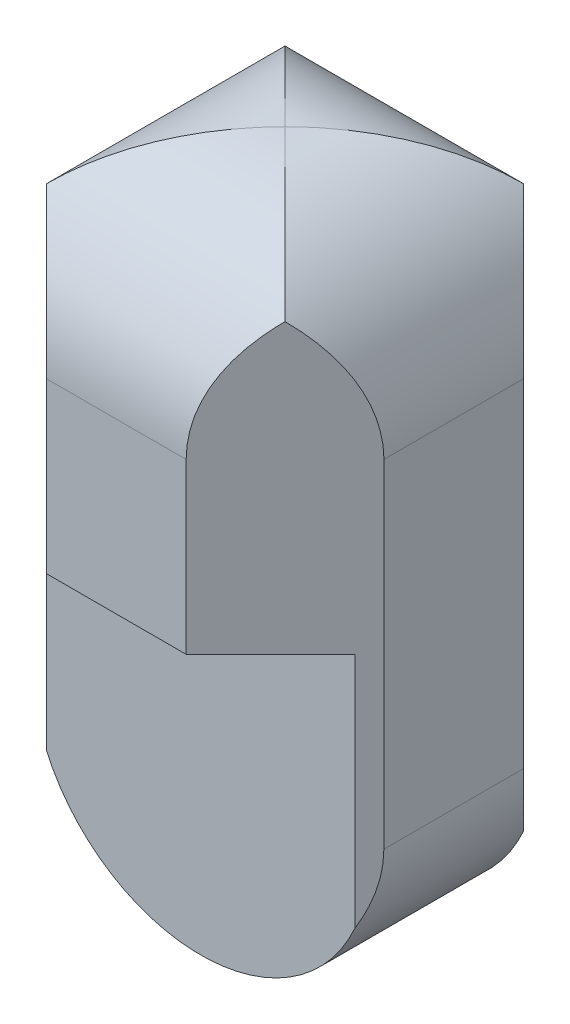
SolidWorks part; units mm, degrees
ref_plane "Front" through (0, 0, 0) normal (0, 0, 1) x (1, 0, 0)
ref_plane "Top" through (0, 0, 0) normal (0, 1, 0) x (1, 0, 0)
ref_plane "Right" through (0, 0, 0) normal (1, 0, 0) x (0, 0, -1)
sketch "草图1" plane through (0, 0, 0) normal (0, 1, 0) x (1, 0, 0)
  line L0 (-12.6518, 0) -> (13.462, 0) construction
  line L1 (0, 11.6722) -> (0, -14.1269) construction
  line L3 (10, 4.1421) -> (4.1421, 10)
  line L4 (4.1421, 10) -> (-4.1421, 10)
  line L5 (-4.1421, 10) -> (-10, 4.1421)
  line L6 (-10, 4.1421) -> (-10, -4.1421)
  line L7 (-10, -4.1421) -> (-4.1421, -10)
  line L8 (-4.1421, -10) -> (4.1421, -10)
  line L9 (4.1421, -10) -> (10, -4.1421)
  line L10 (10, -4.1421) -> (10, 4.1421)
  circle A0 centre (0, 0) radius 10 construction
extrude "凸台-拉伸1" add sketch "草图1" along normal blind 42
sketch "草图2" plane through (0, 0, 10) normal (0, 0, 1) x (1, 0, 0)
  line L0 (0, 0) -> (0, 24) construction
  line L7 (-10, 10) -> (-10, -2.3893)
  line L8 (-10, -2.3893) -> (10, -2.3893)
  line L9 (10, 10) -> (10, -2.3893)
  arc A1 (-10, 10) -> (10, 10) centre (0, 10) ccw
extrude "切除-拉伸1" cut sketch "草图2" against normal blind 66
sketch "草图4" plane through (0, 0, 10) normal (0, 0, 1) x (1, 0, 0)
  line L0 (10, 42) -> (10, 10) construction
  line L2 (-10, 10) -> (-10, 20)
  line L3 (-10, 20) -> (10, 20)
  line L4 (10, 10) -> (10, 20)
  arc A0 (-10, 10) -> (10, 10) centre (0, 10) ccw
extrude "切除-拉伸2" cut sketch "草图4" against normal blind 5
sketch "草图5" plane through (0, 0, -10) normal (0, 0, -1) x (-1, 0, 0)
  line L0 (10, 42) -> (10, 10) construction
  line L2 (-10, 10) -> (-10, 20)
  line L3 (-10, 20) -> (10, 20)
  line L4 (10, 10) -> (10, 20)
  arc A0 (-10, 10) -> (10, 10) centre (0, 10) ccw
extrude "切除-拉伸3" cut sketch "草图5" against normal blind 5
sketch "草图7" plane through (0, 0, 10) normal (0, 0, 1) x (1, 0, 0)
  line L0 (0, 42) -> (0, 0) construction
  line L1 (-4.1421, 42) -> (4.1421, 42) construction
  line L4 (-10, 30) -> (-10, 44.8839)
  line L5 (-10, 44.8839) -> (10, 44.8839)
  line L6 (10, 30) -> (10, 44.8839)
  arc A0 (10, 30) -> (-10, 30) centre (0, 30) ccw
extrude "切除-拉伸5" cut sketch "草图7" against normal blind 30
sketch "草图8" plane through (10, 0, 0) normal (1, 0, 0) x (0, 0, -1)
  line L0 (0, 40) -> (0, 0) construction
  line L1 (10, 40) -> (-10, 40) construction
  line L4 (-10, 30) -> (-10, 44.0756)
  line L5 (-10, 44.0756) -> (10, 44.0756)
  line L6 (10, 30) -> (10, 44.0756)
  arc A0 (10, 30) -> (-10, 30) centre (0, 30) ccw
  dimension "D1" = 10
extrude "切除-拉伸6" cut sketch "草图8" against normal blind 30
